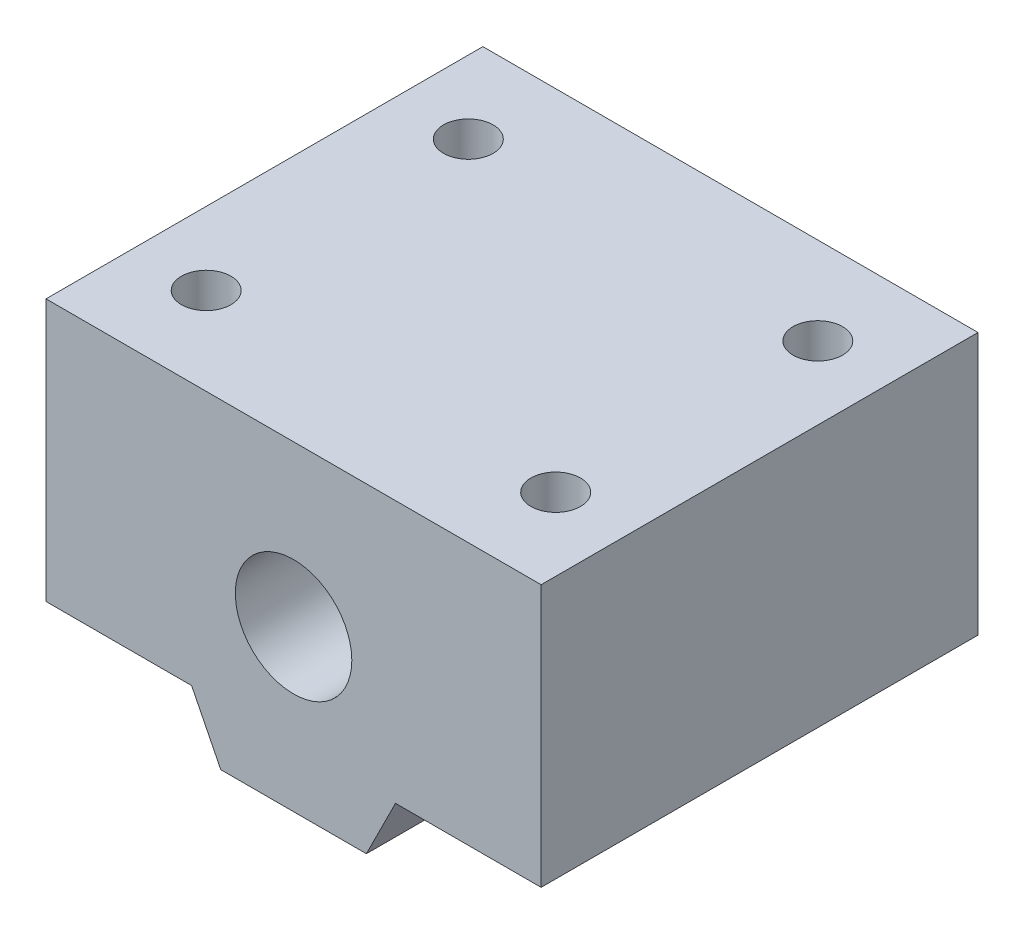
SolidWorks part; units mm, degrees
ref_plane "前视基准面" through (0, 0, 0) normal (0, 0, 1) x (1, 0, 0)
ref_plane "上视基准面" through (0, 0, 0) normal (0, 1, 0) x (1, 0, 0)
ref_plane "右视基准面" through (0, 0, 0) normal (1, 0, 0) x (0, 0, -1)
other "Configuration Table"
sketch "草图1" plane through (0, 0, 0) normal (0, 0, 1) x (1, 0, 0)
  line L0 (-17, -7) -> (-7, -7)
  line L1 (-17, -11) -> (17, -11) construction
  line L2 (-17, -7) -> (-17, 11)
  line L3 (-17, 11) -> (17, 11)
  line L4 (17, -7) -> (17, 11)
  line L5 (-17, -11) -> (17, 11) construction
  line L6 (-17, 11) -> (17, -11) construction
  line L7 (0, 18.3117) -> (0, -21.075) construction
  line L8 (-5, -11) -> (5, -11)
  line L9 (5, -11) -> (7, -7)
  line L10 (-5, -11) -> (-7, -7)
  line L11 (7, -7) -> (17, -7)
  circle A0 centre (0, 0) radius 4
  point P0 (0, 0)
  point P13 (0, -11)
  dimension "D7" = 8
  dimension "D1" = 34
  dimension "D2" = 22
  dimension "D3" = 18
  dimension "D4" = 10
  dimension "D5" = 10
  dimension "D6" = 10
extrude "凸台-拉伸1" add sketch "草图1" along normal blind 30
sketch "草图3" plane through (0, 11, 0) normal (0, 1, 0) x (1, 0, 0)
  line L0 (-17, 0) -> (17, -30) construction
  line L1 (17, 0) -> (-17, -30) construction
  line L3 (-12, -24) -> (12, -24) construction
  line L12 (-12, -24) -> (-12, -6) construction
  line L13 (-12, -6) -> (12, -6) construction
  line L14 (12, -24) -> (12, -6) construction
  line L15 (-12, -24) -> (12, -6) construction
  line L16 (-12, -6) -> (12, -24) construction
  circle A0 centre (12, -6) radius 1.7
  circle A1 centre (-12, -6) radius 1.7
  circle A2 centre (-12, -24) radius 1.7
  circle A3 centre (12, -24) radius 1.7
  point P2 (0, -15)
  dimension "D3" = 3.4
  dimension "D1" = 24
  dimension "D2" = 18
extrude "切除-拉伸1" cut sketch "草图3" against normal blind 30
sketch "草图4" plane through (0, -7, 0) normal (0, -1, 0) x (1, 0, 0)
  circle A0 centre (-12, 24) radius 2
  circle A1 centre (12, 24) radius 2
  circle A2 centre (12, 6) radius 2
  circle A3 centre (-12, 6) radius 2
  dimension "D1" = 4
extrude "切除-拉伸2" cut sketch "草图4" against normal blind 6
